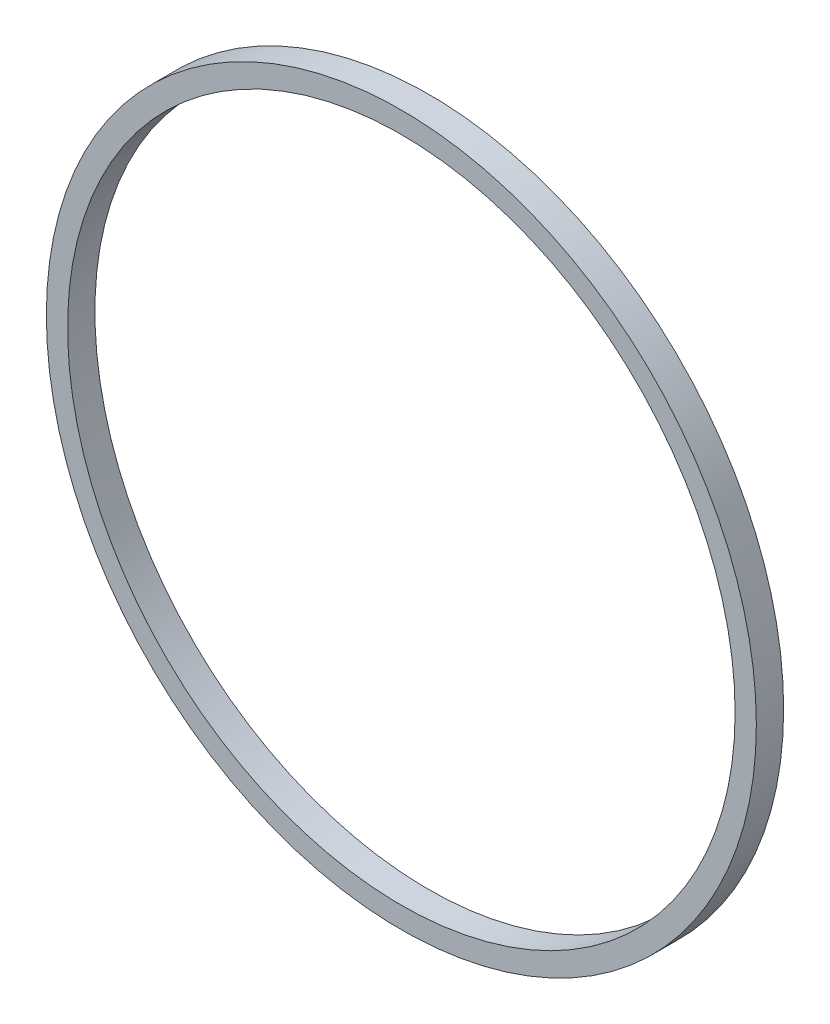
SolidWorks part; units mm, degrees
ref_plane "Front Plane" through (0, 0, 0) normal (0, 0, 1) x (1, 0, 0)
ref_plane "Top Plane" through (0, 0, 0) normal (0, 1, 0) x (1, 0, 0)
ref_plane "Right Plane" through (0, 0, 0) normal (1, 0, 0) x (0, 0, -1)
sketch "Sketch1" plane through (0, 0, 0) normal (0, 0, 1) x (1, 0, 0)
  arc B0 (9.4233, 171.953) -> (5.1903, 15.2885) centre (166.2366, 89.3266) ccw
  arc B1 (13.0798, 10.4448) -> (150.8717, 85.1111) centre (6.2297, 187.5624) ccw
  arc B2 (151.1218, 94.3656) -> (17.5629, 176.3637) centre (1.1585, -0.1256) ccw
  circle B3 centre (57.875, 92.2544) radius 58.5
  circle B4 centre (57.875, 92.2544) radius 55
  circle B5 centre (57.875, 92.2544) radius 59.5
  circle B6 centre (57.875, 92.2544) radius 63
sketch_block_instance "Block1-1"
sketch_block "Block1"
extrude "Boss-Extrude1" add sketch "Sketch1" along normal mid plane 4.5 contours B3 B4
